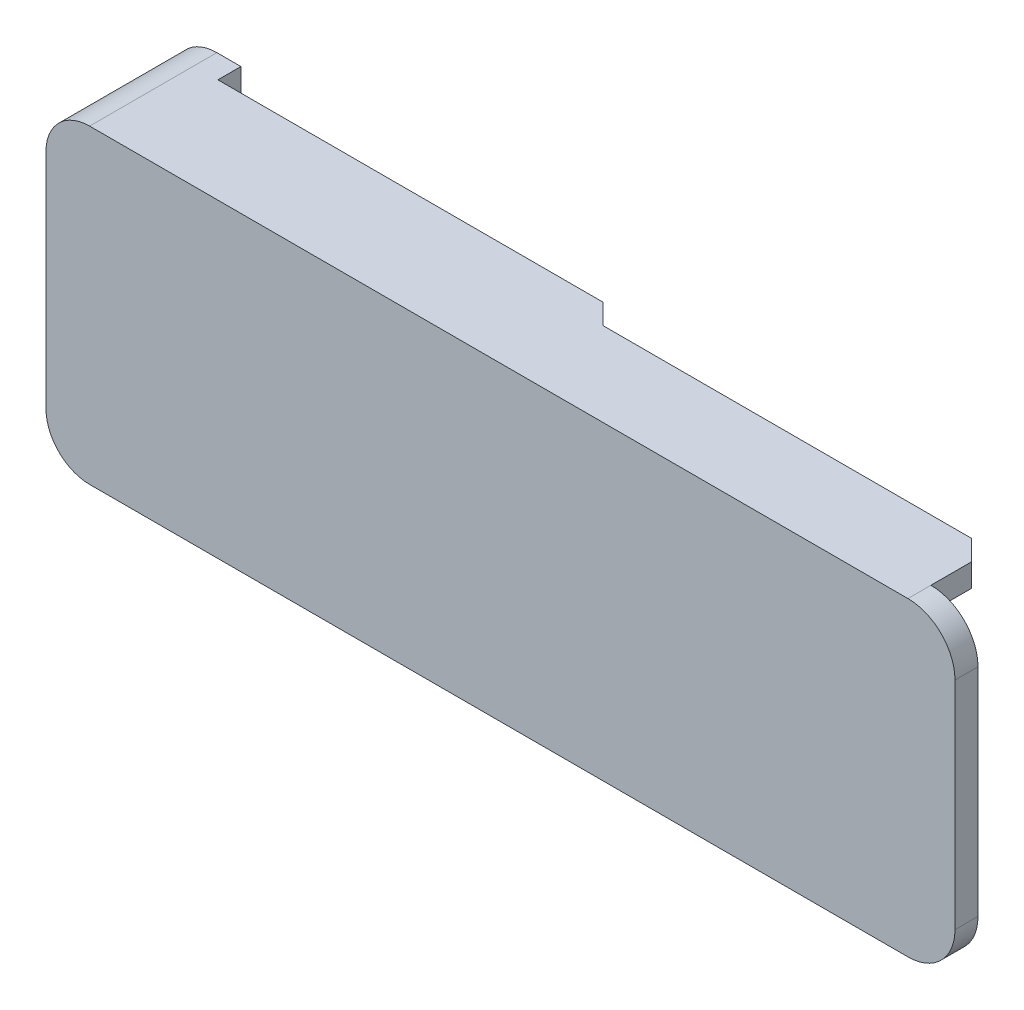
SolidWorks part; units mm, degrees
ref_plane "Front Plane" through (0, 0, 0) normal (0, 0, 1) x (1, 0, 0)
ref_plane "Top Plane" through (0, 0, 0) normal (0, 1, 0) x (1, 0, 0)
ref_plane "Right Plane" through (0, 0, 0) normal (1, 0, 0) x (0, 0, -1)
sketch "Sketch1" plane through (0, 0, 0) normal (0, 0, 1) x (1, 0, 0)
  line L0 (-65.4991, 50.3317) -> (-14.7932, 50.3317)
  line L1 (-5.0472, 50.3317) -> (-14.7932, 50.3317)
  line L2 (-1.5692, 43.9657) -> (-1.5692, 46.8537)
  line L3 (-1.5692, 43.9657) -> (-1.5692, 33.8057)
  line L4 (-1.5692, 33.8057) -> (-1.5692, 30.8817)
  line L5 (-5.0472, 27.4037) -> (-14.8292, 27.4037)
  line L6 (-14.8292, 27.4037) -> (-65.4991, 27.4037)
  line L7 (-68.7232, 30.6278) -> (-68.7232, 47.1076)
  line L62 (-3.2692, 43.9657) -> (-3.2692, 46.8537)
  line L63 (-14.8292, 29.1037) -> (-65.4991, 29.1037)
  line L64 (-67.0232, 30.6278) -> (-67.0232, 47.1076)
  line L65 (-65.4991, 48.6317) -> (-14.7932, 48.6317)
  line L66 (-3.2692, 43.9657) -> (-3.2692, 33.8057)
  line L67 (-5.0472, 48.6317) -> (-14.7932, 48.6317)
  line L68 (-3.2692, 33.8057) -> (-3.2692, 30.8817)
  line L69 (-5.0472, 29.1037) -> (-14.8292, 29.1037)
  arc A0 (-1.5692, 46.8537) -> (-5.0472, 50.3317) centre (-5.0472, 46.8537) ccw
  arc A1 (-1.5692, 30.8817) -> (-5.0472, 27.4037) centre (-5.0472, 30.8817) cw
  arc A2 (-68.7232, 30.6278) -> (-65.4991, 27.4037) centre (-65.4991, 30.6278) ccw
  arc A3 (-65.4991, 50.3317) -> (-68.7232, 47.1076) centre (-65.4991, 47.1076) ccw
  arc A38 (-3.2692, 30.8817) -> (-5.0472, 29.1037) centre (-5.0472, 30.8817) cw
  arc A39 (-3.2692, 46.8537) -> (-5.0472, 48.6317) centre (-5.0472, 46.8537) ccw
  arc A40 (-67.0232, 30.6278) -> (-65.4991, 29.1037) centre (-65.4991, 30.6278) ccw
  arc A41 (-65.4991, 48.6317) -> (-67.0232, 47.1076) centre (-65.4991, 47.1076) ccw
  dimension "D1" = 1.778
  dimension "D2" = 1.7
extrude "Boss-Extrude1" add sketch "Sketch1" against normal blind 6
sketch "Sketch3" plane through (0, 0, 0) normal (0, 0, 1) x (1, 0, 0)
  line L0 (-68.7232, 47.1076) -> (-68.7232, 30.6278) construction
  line L1 (-5.0472, 50.3317) -> (-65.4991, 50.3317) construction
  line L2 (-1.5692, 30.8817) -> (-1.5692, 46.8537) construction
  line L3 (-65.4991, 27.4037) -> (-5.0472, 27.4037) construction
  line L4 (-68.7232, 47.1076) -> (-68.7232, 30.6278)
  line L5 (-5.0472, 50.3317) -> (-65.4991, 50.3317)
  line L6 (-1.5692, 30.8817) -> (-1.5692, 46.8537)
  line L7 (-65.4991, 27.4037) -> (-5.0472, 27.4037)
  arc A0 (-68.7232, 30.6278) -> (-65.4991, 27.4037) centre (-65.4991, 30.6278) ccw construction
  arc A1 (-65.4991, 50.3317) -> (-68.7232, 47.1076) centre (-65.4991, 47.1076) ccw construction
  arc A2 (-1.5692, 46.8537) -> (-5.0472, 50.3317) centre (-5.0472, 46.8537) ccw construction
  arc A3 (-5.0472, 27.4037) -> (-1.5692, 30.8817) centre (-5.0472, 30.8817) ccw construction
  arc A4 (-68.7232, 30.6278) -> (-65.4991, 27.4037) centre (-65.4991, 30.6278) ccw
  arc A5 (-65.4991, 50.3317) -> (-68.7232, 47.1076) centre (-65.4991, 47.1076) ccw
  arc A6 (-1.5692, 46.8537) -> (-5.0472, 50.3317) centre (-5.0472, 46.8537) ccw
  arc A7 (-5.0472, 27.4037) -> (-1.5692, 30.8817) centre (-5.0472, 30.8817) ccw
extrude "Boss-Extrude2" add sketch "Sketch3" along normal blind 1.7
sketch "Sketch5" plane through (0, 48.6317, 0) normal (0, -1, 0) x (-1, 0, 0)
  line L0 (5.0472, 6) -> (65.4991, 6) construction
  line L1 (5.0472, 6) -> (5.0472, 0) construction
  circle A0 centre (7.0472, 4) radius 1
  dimension "D1" = 2
  dimension "D2" = 2
  dimension "D3" = 2
extrude "Boss-Extrude3" [suppressed] add sketch "Sketch5" along normal blind 1
sketch "Sketch6" [suppressed] plane through (0, 47.6317, 0) normal (0, -1, 0) x (-1, 0, 0)
  line L0 (7.0472, 4) -> (8.0472, 4) construction
  circle A0 centre (7.0472, 4) radius 1 construction
ref_plane "Plane4" [suppressed] through (0, 0, -4) normal (0, 0, -1) x (-1, 0, 0)
sketch "Sketch7" [suppressed] plane through (0, 0, -4) normal (0, 0, -1) x (-1, 0, 0)
  line L0 (7.0472, 47.6317) -> (7.0472, 48.6317) construction
  line L1 (6.0472, 48.6317) -> (8.0472, 48.6317)
  line L2 (7.0472, 47.6317) -> (8.0472, 47.6317)
  line L3 (8.0472, 47.6317) -> (8.0472, 48.6317)
  arc A0 (6.0472, 48.6317) -> (8.0472, 48.6317) centre (7.0472, 48.6317) ccw
  point P0 (7.0472, 47.6317)
  point P8 (7.0472, 48.6317)
ref_plane "Plane5" through (0, 0, -4) normal (0, 0, -1) x (-1, 0, 0)
ref_plane "Plane6" through (0, 38.8677, 0) normal (0, -1, 0) x (-1, 0, 0)
sketch "Sketch11" plane through (0, 50.3317, 0) normal (0, 1, 0) x (1, 0, 0)
  line L0 (-35.2731, 6) -> (-33.7731, 4.5)
  line L1 (-5.0472, 6) -> (-65.4991, 6) construction
  line L2 (-33.7731, 4.5) -> (-6.5472, 4.5)
  line L3 (-5.0472, 6) -> (-5.0472, -1.7) construction
  line L4 (-35.2731, 6) -> (-1.5692, 6)
  line L7 (-5.0472, 3) -> (-5.0472, 0)
  line L8 (-1.5692, 6) -> (-1.5692, -1.7) construction
  line L9 (-1.5692, 6) -> (-1.5692, 0)
  line L10 (-5.0472, 0) -> (-1.5692, 0)
  line L11 (-5.0472, -1.7) -> (-65.4991, -1.7) construction
  line L12 (-6.5472, 4.5) -> (-5.0472, 3)
  dimension "D1" = 45
  dimension "D2" = 1.5
  dimension "D3" = 1.7
  dimension "D4" = 1.5
  dimension "D5" = 1.5
extrude "Cut-Extrude3" cut sketch "Sketch11" against normal blind 29
ref_plane "Plane7" through (0, 0, -2.25) normal (0, 0, -1) x (-1, 0, 0)
sketch "Sketch13" plane through (0, 0, -2.25) normal (0, 0, -1) x (-1, 0, 0)
  line L0 (6.5472, 29.1037) -> (33.7731, 29.1037) construction
  line L1 (6.5472, 29.1037) -> (33.7731, 29.1037) construction
  line L2 (8.5472, 29.1037) -> (8.5472, 30.1037)
  line L3 (8.5472, 29.1037) -> (9.5472, 29.1037)
  arc A0 (9.5472, 29.1037) -> (8.5472, 30.1037) centre (8.5472, 29.1037) ccw
  dimension "D1" = 1
  dimension "D4" = 1
  dimension "D2" = 1
  dimension "D3" = 2
revolve "Revolve3" add sketch "Sketch13" angle 360 about L2
mirror "Mirror3" about plane through (0, 38.8677, 0) normal (0, -1, 0) of "Revolve3"
sketch "Sketch14" plane through (0, 0, -6) normal (0, 0, -1) x (-1, 0, 0)
  line L0 (63.7232, 27.4037) -> (63.7232, 50.3317)
  line L1 (65.4991, 27.4037) -> (35.2731, 27.4037) construction
  line L2 (35.2731, 50.3317) -> (65.4991, 50.3317) construction
  line L3 (68.7232, 47.1076) -> (68.7232, 30.6278) construction
  line L4 (68.7232, 47.1076) -> (68.7232, 30.6278)
  line L5 (65.4991, 27.4037) -> (63.7232, 27.4037)
  line L6 (65.4991, 50.3317) -> (63.7232, 50.3317)
  arc A0 (68.7232, 47.1076) -> (65.4991, 50.3317) centre (65.4991, 47.1076) ccw construction
  arc A1 (65.4991, 27.4037) -> (68.7232, 30.6278) centre (65.4991, 30.6278) ccw construction
  arc A2 (68.7232, 47.1076) -> (65.4991, 50.3317) centre (65.4991, 47.1076) ccw
  arc A3 (65.4991, 27.4037) -> (68.7232, 30.6278) centre (65.4991, 30.6278) ccw
  dimension "D1" = 5
extrude "Boss-Extrude5" add sketch "Sketch14" along normal blind 1.7
sketch "Sketch15" plane through (-68.7232, 0, 0) normal (-1, 0, 0) x (0, 0, 1)
  line L0 (-2.3418, 30.6278) -> (-2.3418, 47.1076)
  line L1 (-7.7, 30.6278) -> (1.7, 30.6278) construction
  line L2 (-7.7, 47.1076) -> (1.7, 47.1076) construction
  line L3 (1.7, 47.1076) -> (1.7, 30.6278) construction
  circle A0 centre (-2.3418, 36.6434) radius 1.075
  circle A1 centre (-2.3418, 41.108) radius 1.075
  point P8 (-2.3418, 36.6087)
  point P11 (1.7, 38.8677)
  point P12 (-2.3418, 36.6434)
  point P15 (0, 0)
  point P16 (-2.3418, 41.108)
  dimension "D1" = 4.0418
  dimension "D2" = 2.15
extrude "Cut-Extrude4" cut sketch "Sketch15" against normal through all contours L0 A1 | L0 A1 | L0 A0 | L0 A0
sketch "Sketch17" plane through (0, 0, 0) normal (0, 0, -1) x (-1, 0, 0)
  circle A1 centre (14.9042, 32.6417) radius 1.46 construction
  circle A3 centre (60.9822, 45.2187) radius 1.46 construction
  circle A4 centre (14.9042, 32.6417) radius 1.45
  circle A5 centre (60.9822, 45.2187) radius 1.45
  dimension "D1" = 2.9
  dimension "D2" = 2.9
extrude "Boss-Extrude6" add sketch "Sketch17" along normal blind 2
